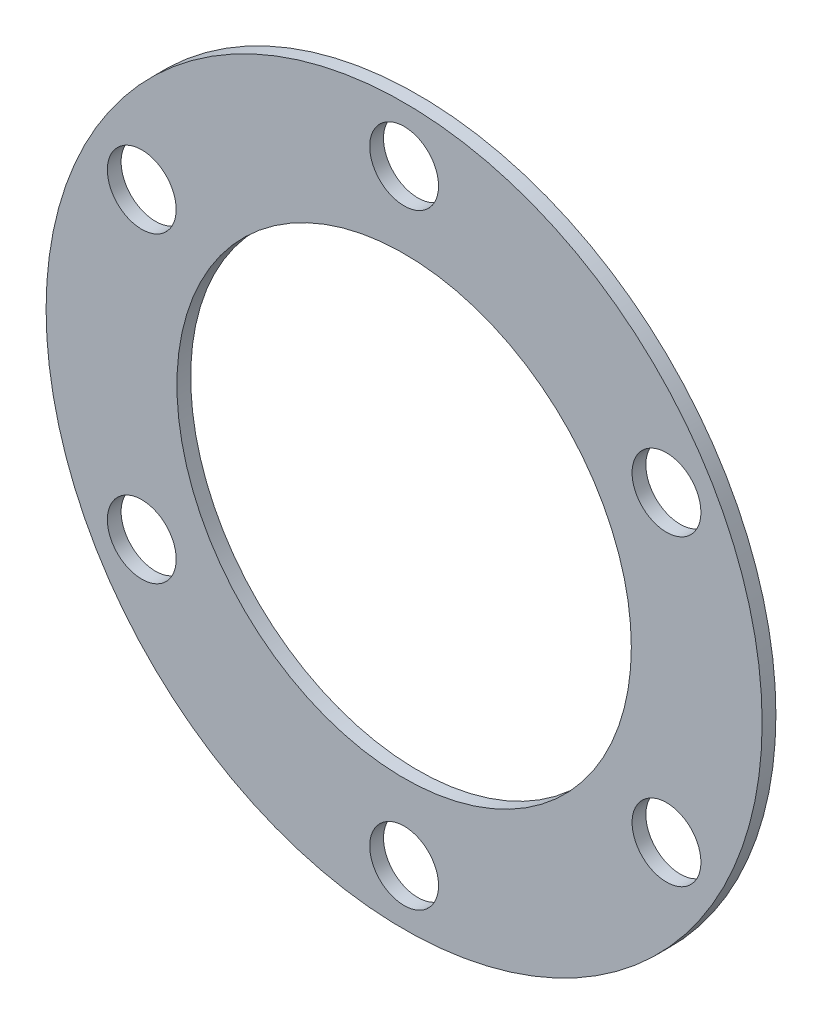
SolidWorks part; units mm, degrees
ref_plane "Plan de face" through (0, 0, 0) normal (0, 0, 1) x (1, 0, 0)
ref_plane "Plan de dessus" through (0, 0, 0) normal (0, 1, 0) x (1, 0, 0)
ref_plane "Plan de droite" through (0, 0, 0) normal (1, 0, 0) x (0, 0, -1)
sketch "Esquisse1" plane through (0, 0, 0) normal (0, 0, 1) x (1, 0, 0)
  circle A1 centre (0, 22) radius 2.5
  circle A2 centre (0, 0) radius 26
  circle A3 centre (19.0531, 11.0009) radius 2.5
  circle A4 centre (19.0541, -10.9991) radius 2.5
  circle A5 centre (0.002, -22) radius 2.5
  circle A6 centre (-19.0511, -11.0009) radius 2.5
  circle A7 centre (-19.0521, 10.9991) radius 2.5
  circle A8 centre (0, 0) radius 16.5
  point P18 (0.001, 0)
  dimension "D2" = 33
  dimension "D1" = 6
extrude "Boss.-Extru.1" add sketch "Esquisse1" along normal blind 1
